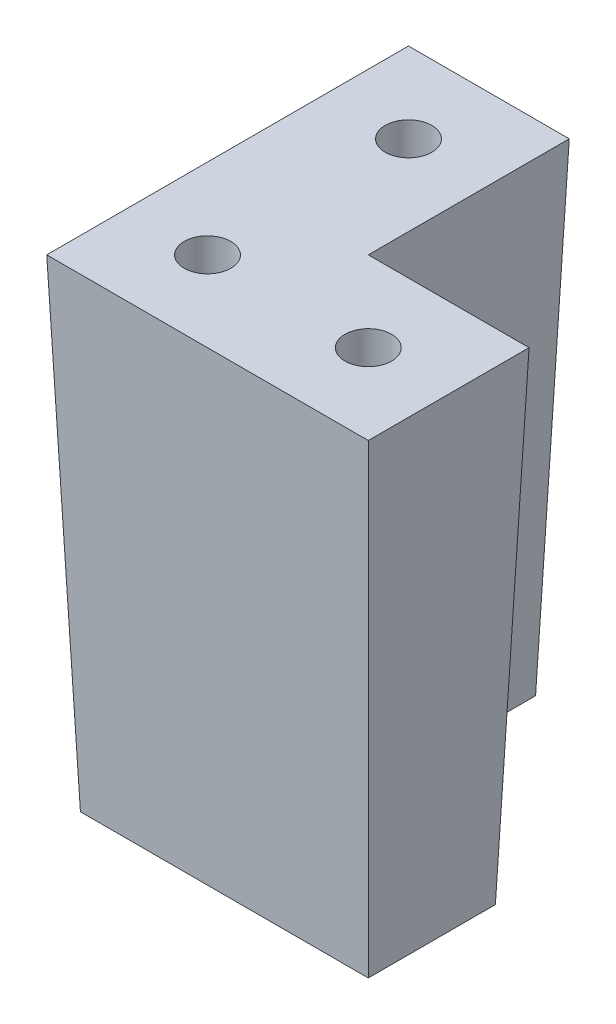
SolidWorks part; units mm, degrees
ref_plane "Front Plane" through (0, 0, 0) normal (0, 0, 1) x (1, 0, 0)
ref_plane "Top Plane" through (0, 0, 0) normal (0, 1, 0) x (1, 0, 0)
ref_plane "Right Plane" through (0, 0, 0) normal (1, 0, 0) x (0, 0, -1)
sketch "Sketch1" plane through (0, 0, 0) normal (0, 1, 0) x (1, 0, 0)
  line L0 (-960, 10) -> (49040, 10) construction
  line L1 (0, 0) -> (40, 0)
  line L2 (0, 0) -> (0, 45)
  line L3 (0, 45) -> (20, 45)
  line L4 (40, 0) -> (40, 20)
  line L7 (40, 20) -> (20, 20)
  line L8 (20, 45) -> (20, 20)
  line L9 (10, -955) -> (10, 49045) construction
  point P10 (40, 10)
  point P13 (10, 45)
  dimension "D2" = 45
  dimension "D3" = 20
  dimension "D4" = 20
extrude "Boss-Extrude1" add sketch "Sketch1" against normal blind 60 draft 2
hole_wizard "CBORE for M5 SBHCS1" positions "Sketch2" profile "Sketch3" counterbore size "M5" standard "ANSI Metric" end condition through all
sketch "Sketch2" plane through (0, -60, 0) normal (0, -1, 0) x (-1, 0, 0)
  line L0 (200960, 10) -> (-249040, 10) construction
  line L1 (-10, -200955) -> (-10, 249045) construction
  line L2 (-40, 0) -> (-40, 20) construction
  line L3 (0, 45) -> (-20, 45) construction
  point P0 (-10, 10)
  point P6 (-30, 10)
  point P8 (-10, 35)
  dimension "D1" = 10
  dimension "D2" = 10
sketch "Sketch3" plane through (10, -60, -10) normal (1, 0, 0) x (0, 0, -1)
  line L0 (0, 0) -> (0, 60)
  line L1 (0, 60) -> (2.9, 60)
  line L3 (2.9, 60) -> (2.9, 55)
  line L4 (2.9, 55) -> (5.75, 55)
  line L5 (5.75, 55) -> (5.75, 0)
  line L7 (5.75, 0) -> (0, 0)
  line L11 (0, -6.35) -> (0, 107.95) construction
  dimension "Thru Hole Dia." = 5.8
  dimension "Thru Hole Depth" = 60
  dimension "C'Bore Dia." = 11.5
  dimension "C'Bore Depth" = 55
